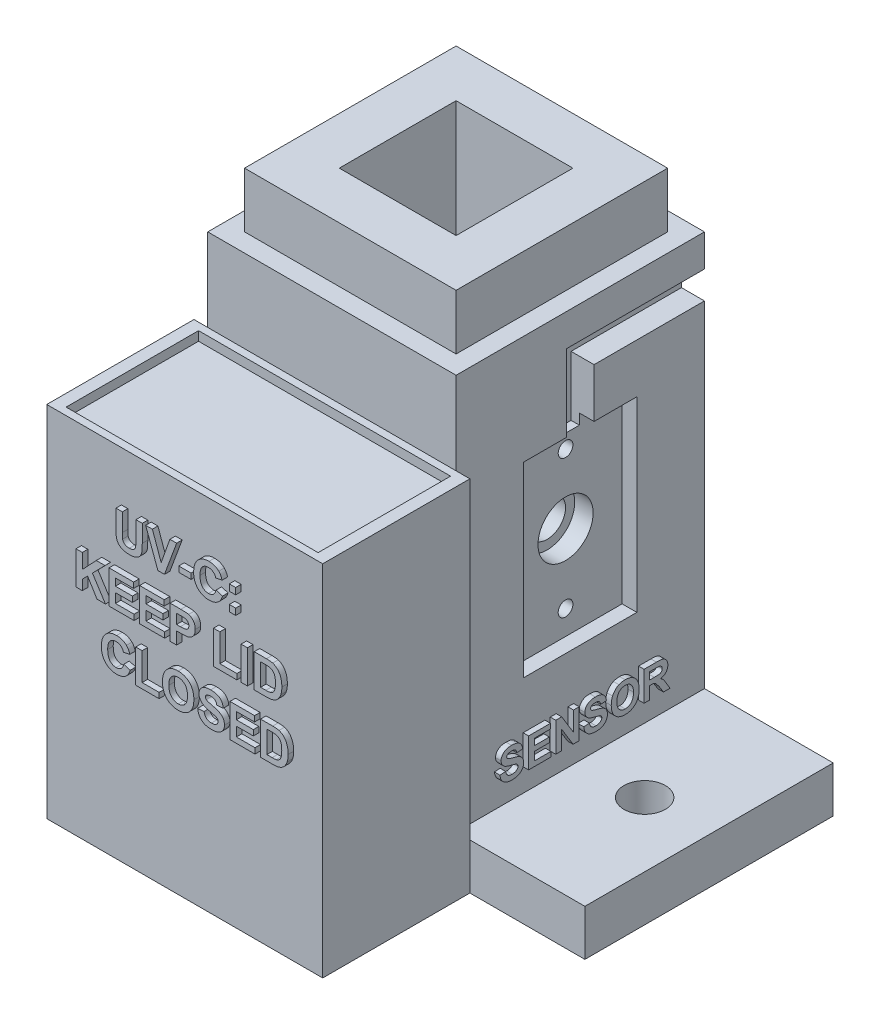
SolidWorks part; units mm, degrees
material "PETG"
ref_plane "Front Plane" through (0, 0, 0) normal (0, 0, 1) x (1, 0, 0)
ref_plane "Top Plane" through (0, 0, 0) normal (0, 1, 0) x (1, 0, 0)
ref_plane "Right Plane" through (0, 0, 0) normal (1, 0, 0) x (0, 0, -1)
other "Configuration Table"
sketch "Sketch1" plane through (0, 0, 0) normal (0, 1, 0) x (1, 0, 0)
  line L1 (-13.5, -13.5) -> (13.5, -13.5)
  line L2 (-13.5, -13.5) -> (-13.5, 13.5)
  line L3 (-13.5, 13.5) -> (13.5, 13.5)
  line L4 (13.5, -13.5) -> (13.5, 13.5)
  line L5 (-13.5, -13.5) -> (13.5, 13.5) construction
  line L6 (-13.5, 13.5) -> (13.5, -13.5) construction
  point P6 (0, 0)
  dimension "D1" = 27
  dimension "D2" = 27
extrude "Block" add sketch "Sketch1" along normal blind 54
sketch "Sketch2" plane through (0, 0, 0) normal (0, 1, 0) x (1, 0, 0)
  line L0 (-15, -29.5) -> (15, -29.5)
  line L1 (15, -29.5) -> (15, -13.5)
  line L2 (15, -13.5) -> (-15, -13.5)
  line L3 (-15, -13.5) -> (-15, -29.5)
extrude "Switch_Pillar" add sketch "Sketch2" along normal blind 39
sketch "Sketch3" plane through (0, 0, 0) normal (0, 1, 0) x (1, 0, 0)
  line L1 (-6.35, -6.35) -> (6.35, -6.35)
  line L2 (-6.35, -6.35) -> (-6.35, 6.35)
  line L3 (-6.35, 6.35) -> (6.35, 6.35)
  line L4 (6.35, -6.35) -> (6.35, 6.35)
  line L5 (-6.35, -6.35) -> (6.35, 6.35) construction
  line L6 (-6.35, 6.35) -> (6.35, -6.35) construction
  point P6 (0, 0)
  dimension "D1" = 12.7
  dimension "D2" = 12.7
extrude "Cuvette_Pocket" cut sketch "Sketch3" against normal blind 40 from offset 54
sketch "Sketch4" plane through (0, 0, 0) normal (0, 1, 0) x (1, 0, 0)
  line L0 (-18.5, -18.5) -> (18.5, -18.5)
  line L1 (18.5, -18.5) -> (18.5, 18.5)
  line L2 (18.5, 18.5) -> (-18.5, 18.5)
  line L3 (-18.5, 18.5) -> (-18.5, -18.5)
  line L4 (-11.5, -11.5) -> (11.5, -11.5)
  line L5 (11.5, -11.5) -> (11.5, 11.5)
  line L6 (11.5, 11.5) -> (-11.5, 11.5)
  line L7 (-11.5, 11.5) -> (-11.5, -11.5)
extrude "Lid_Step" cut sketch "Sketch4" against normal blind 6 from offset 54
sketch "Sketch5" plane through (0, 0, 0) normal (1, 0, 0) x (0, 0, -1)
  circle A0 centre (0, 26) radius 2
  dimension "D1" = 4
extrude "Optical_Apertures" cut sketch "Sketch5" along normal through all and the other way through all
sketch "Sketch6" plane through (0, 0, 0) normal (1, 0, 0) x (0, 0, -1)
  line L1 (-10.15, 15.85) -> (10.15, 15.85)
  line L2 (-10.15, 15.85) -> (-10.15, 36.15)
  line L3 (-10.15, 36.15) -> (10.15, 36.15)
  line L4 (10.15, 15.85) -> (10.15, 36.15)
  line L5 (-10.15, 15.85) -> (10.15, 36.15) construction
  line L6 (-10.15, 36.15) -> (10.15, 15.85) construction
  point P5 (0, 26)
  dimension "D1" = 20.3
  dimension "D2" = 20.3
extrude "LED_Recess" cut sketch "Sketch6" along normal blind 1.6 from offset 13.5
sketch "Sketch7" plane through (0, 0, 0) normal (1, 0, 0) x (0, 0, -1)
  line L1 (-6.15, 15.85) -> (6.15, 15.85)
  line L2 (-6.15, 15.85) -> (-6.15, 36.15)
  line L3 (-6.15, 36.15) -> (6.15, 36.15)
  line L4 (6.15, 15.85) -> (6.15, 36.15)
  line L5 (-6.15, 15.85) -> (6.15, 36.15) construction
  line L6 (-6.15, 36.15) -> (6.15, 15.85) construction
  point P5 (0, 26)
  dimension "D2" = 20.3
  dimension "D1" = 12.3
extrude "GUVA_Recess" cut sketch "Sketch7" against normal blind 1.6 from offset 13.5
sketch "Sketch8" plane through (0, 0, 0) normal (1, 0, 0) x (0, 0, -1)
  circle A0 centre (0, 26) radius 3
  dimension "D1" = 6
extrude "LED_Relief" cut sketch "Sketch8" along normal blind 2 from offset 11.9
sketch "Sketch9" plane through (0, 0, 0) normal (1, 0, 0) x (0, 0, -1)
  circle A0 centre (0, 26) radius 3
  dimension "D1" = 6
extrude "Sensor_Relief" cut sketch "Sketch9" against normal blind 2 from offset 11.9
sketch "Sketch10" plane through (0, 0, 0) normal (1, 0, 0) x (0, 0, -1)
  circle A0 centre (7, 19) radius 0.8
  circle A1 centre (-7, 33) radius 0.8
  dimension "D1" = 1.6
  dimension "D2" = 1.6
extrude "LED_Screw_Holes_M2" cut sketch "Sketch10" along normal blind 4 from offset 11.9
sketch "Sketch11" plane through (0, 0, 0) normal (1, 0, 0) x (0, 0, -1)
  circle A0 centre (0, 18.5) radius 0.8
  circle A1 centre (0, 33.5) radius 0.8
  dimension "D1" = 1.6
  dimension "D2" = 1.6
extrude "GUVA_Screw_Holes_M2" cut sketch "Sketch11" against normal blind 4 from offset 11.9
sketch "Sketch12" plane through (0, 0, 0) normal (1, 0, 0) x (0, 0, -1)
  line L0 (-1.5, 35) -> (-1.5, 44.5)
  line L1 (-1.5, 44.5) -> (14.5, 44.5)
  line L2 (14.5, 44.5) -> (14.5, 41.5)
  line L3 (14.5, 41.5) -> (1.5, 41.5)
  line L4 (1.5, 41.5) -> (1.5, 35)
  line L5 (1.5, 35) -> (-1.5, 35)
extrude "LED_Cable_Slot" cut sketch "Sketch12" along normal blind 2.5 from offset 13.5
sketch "Sketch13" plane through (0, 0, 0) normal (1, 0, 0) x (0, 0, -1)
  line L0 (-1.5, 35) -> (-1.5, 44.5)
  line L1 (-1.5, 44.5) -> (14.5, 44.5)
  line L2 (14.5, 44.5) -> (14.5, 41.5)
  line L3 (14.5, 41.5) -> (1.5, 41.5)
  line L4 (1.5, 41.5) -> (1.5, 35)
  line L5 (1.5, 35) -> (-1.5, 35)
extrude "GUVA_Cable_Slot" cut sketch "Sketch13" against normal blind 2.5 from offset 13.5
sketch "Sketch14" plane through (0, 0, 0) normal (0, 1, 0) x (1, 0, 0)
  line L1 (-13.7, -28.7) -> (13.7, -28.7)
  line L2 (-13.7, -28.7) -> (-13.7, -14.3)
  line L3 (-13.7, -14.3) -> (13.7, -14.3)
  line L4 (13.7, -28.7) -> (13.7, -14.3)
  line L5 (-13.7, -28.7) -> (13.7, -14.3) construction
  line L6 (-13.7, -14.3) -> (13.7, -28.7) construction
  point P5 (0, -21.5)
  dimension "D1" = 27.4
  dimension "D2" = 14.4
extrude "Reed_Switch_Seat" cut sketch "Sketch14" against normal blind 1 from offset 39
sketch "Sketch15" plane through (0, 0, 0) normal (0, 1, 0) x (1, 0, 0)
  line L0 (-27.5, -13.5) -> (-13.5, -13.5)
  line L1 (-13.5, -13.5) -> (-13.5, 13.5)
  line L2 (-13.5, 13.5) -> (-27.5, 13.5)
  line L3 (-27.5, 13.5) -> (-27.5, -13.5)
extrude "Foot_Left" add sketch "Sketch15" along normal blind 5
sketch "Sketch16" plane through (0, 0, 0) normal (0, 1, 0) x (1, 0, 0)
  line L0 (13.5, -13.5) -> (27.5, -13.5)
  line L1 (27.5, -13.5) -> (27.5, 13.5)
  line L2 (27.5, 13.5) -> (13.5, 13.5)
  line L3 (13.5, 13.5) -> (13.5, -13.5)
extrude "Foot_Right" add sketch "Sketch16" along normal blind 5
sketch "Sketch17" plane through (0, 0, 0) normal (0, 1, 0) x (1, 0, 0)
  circle A0 centre (-20.5, 0) radius 2.25
  circle A1 centre (20.5, 0) radius 2.25
  dimension "D1" = 4.5
  dimension "D2" = 4.5
extrude "Foot_Holes_M4" cut sketch "Sketch17" along normal blind 6 from offset 0.5
sketch "Sketch18" plane through (0, 0, 0) normal (1, 0, 0) x (0, 0, -1)
  text T0 "UV LED" font "Arial" height 3.2
extrude "Label_UV_LED" add sketch "Sketch18" against normal blind 0.6 from offset 13.5
sketch "Sketch19" plane through (0, 0, 0) normal (1, 0, 0) x (0, 0, -1)
  text T0 "SENSOR" font "Arial" height 3.2
extrude "Label_SENSOR" add sketch "Sketch19" along normal blind 0.6 from offset 13.5
sketch "Sketch20" plane through (0, 0, 0) normal (0, 0, 1) x (1, 0, 0)
  text T0 "UV-C:" font "Arial" height 3.6
extrude "Label_Warning_1" add sketch "Sketch20" along normal blind 0.6 from offset 29.5
sketch "Sketch21" plane through (0, 0, 0) normal (0, 0, 1) x (1, 0, 0)
  text T0 "KEEP LID" font "Arial" height 3.6
extrude "Label_Warning_2" add sketch "Sketch21" along normal blind 0.6 from offset 29.5
sketch "Sketch22" plane through (0, 0, 0) normal (0, 0, 1) x (1, 0, 0)
  text T0 "CLOSED" font "Arial" height 3.6
extrude "Label_Warning_3" add sketch "Sketch22" along normal blind 0.6 from offset 29.5
equation "\"Jar_OD\"= 90  'ASSUMED - Part G fallback - jar outer diameter"
equation "\"Jar_H\"= 120  'ASSUMED - Part G fallback - jar height"
equation "\"Pump_L\"= 45  'ASSUMED - Part G fallback"
equation "\"Pump_W\"= 24  'ASSUMED - Part G fallback"
equation "\"Pump_H\"= 33  'ASSUMED - Part G fallback"
equation "\"Pump_Outlet_OD\"= 7.5  'ASSUMED - Part G fallback"
equation "\"Tube_OD\"= 8  'ASSUMED - Part G fallback"
equation "\"Tube_ID\"= 6  'ASSUMED - Part G fallback"
equation "\"TDS_Body_Dia\"= 12  'ASSUMED - Part G fallback"
equation "\"TDS_Wet_Len\"= 45  'ASSUMED - Part G fallback - length in water"
equation "\"DS_Tube_Dia\"= 6  'ASSUMED - Part G fallback"
equation "\"DS_Tube_Len\"= 50  'ASSUMED - Part G fallback"
equation "\"ORP_Body_Dia\"= 12  'ASSUMED - Part G fallback"
equation "\"ORP_Body_Len\"= 150  'ASSUMED - Part G fallback"
equation "\"ORP_Cap_Dia\"= 16  'ASSUMED - Part G fallback"
equation "\"Turb_W\"= 33  'ASSUMED - Part G fallback - head width"
equation "\"Turb_D\"= 28  'ASSUMED - Part G fallback - head depth"
equation "\"Turb_H\"= 30  'ASSUMED - Part G fallback - head height"
equation "\"Turb_Slot_W\"= 10  'ASSUMED - Part G fallback - slot width"
equation "\"Flow_L\"= 62  'ASSUMED - Part G fallback YF-S201"
equation "\"Flow_W\"= 36  'ASSUMED - Part G fallback"
equation "\"Flow_H\"= 35  'ASSUMED - Part G fallback"
equation "\"Thread_G12_OD\"= 20.955  'ASSUMED - Part G fallback thread G1/2 (major diameter)"
equation "\"Valve_L\"= 75  'ASSUMED - Part G fallback"
equation "\"Valve_W\"= 45  'ASSUMED - Part G fallback"
equation "\"Valve_H\"= 60  'ASSUMED - Part G fallback"
equation "\"Tee_L\"= 40  'ASSUMED - Part G fallback - overall length"
equation "\"Tee_Branch_L\"= 25  'ASSUMED - Part G fallback"
equation "\"Tee_OD\"= 12  'ASSUMED - Part G fallback"
equation "\"Cuv_W\"= 12.5  'ASSUMED - old R3 cuvette (station suppressed in SS4)"
equation "\"Cuv_D\"= 12.5  'ASSUMED - old R3 cuvette (station suppressed in SS4)"
equation "\"Cuv_H\"= 45  'ASSUMED - old R3 cuvette (station suppressed in SS4)"
equation "\"LED_Board_L\"= 20  'ASSUMED - Part G fallback"
equation "\"LED_Board_W\"= 20  'ASSUMED - Part G fallback - LED at centre"
equation "\"GUVA_L\"= 20  'ASSUMED - Part G fallback"
equation "\"GUVA_W\"= 12  'ASSUMED - Part G fallback - sensor at centre"
equation "\"Reed_L\"= 27  'ASSUMED - Part G fallback MC-38 half"
equation "\"Reed_W\"= 14  'ASSUMED - Part G fallback"
equation "\"Reed_H\"= 8  'ASSUMED - Part G fallback"
equation "\"ESP_L\"= 51  'ASSUMED - Part G fallback"
equation "\"ESP_W\"= 28  'ASSUMED - Part G fallback"
equation "\"TFT_L\"= 58  'ASSUMED - Part G fallback - board"
equation "\"TFT_W\"= 35  'ASSUMED - Part G fallback - board"
equation "\"TFT_Win_L\"= 35  'ASSUMED - Part G fallback - visible window"
equation "\"TFT_Win_W\"= 28  'ASSUMED - Part G fallback - visible window"
equation "\"Relay_L\"= 50  'ASSUMED - Part G fallback"
equation "\"Relay_W\"= 26  'ASSUMED - Part G fallback"
equation "\"Relay_H\"= 19  'ASSUMED - Part G fallback"
equation "\"Mosfet_L\"= 34  'ASSUMED - Part G fallback"
equation "\"Mosfet_W\"= 17  'ASSUMED - Part G fallback"
equation "\"Mosfet_H\"= 12  'ASSUMED - Part G fallback"
equation "\"TDS_Board_L\"= 42  'ASSUMED - Part G fallback"
equation "\"TDS_Board_W\"= 32  'ASSUMED - Part G fallback"
equation "\"Turb_Board_L\"= 38  'ASSUMED - Part G fallback"
equation "\"Turb_Board_W\"= 28  'ASSUMED - Part G fallback"
equation "\"BNC_Thread_Dia\"= 9.5  'ASSUMED - Part G fallback"
equation "\"Plate_L\"= 420  'ASSUMED - Part G fallback"
equation "\"Plate_W\"= 297  'ASSUMED - Part G fallback"
equation "\"Plate_T\"= 6  'ASSUMED - Part G fallback"
equation "\"Probe_Clr\"= 0.3  'DESIGN VALUE - Part C rule 3 - printed probe hole = diameter + 0.3"
equation "\"Cuv_Clr\"= 0.2  'DESIGN VALUE - Part C rule 3 - cuvette pocket = size + 0.2"
equation "\"Label_H\"= 0.6  'DESIGN VALUE - Part D - raised label height"
equation "\"D1@Sketch1\" = 27.0"
equation "\"D2@Sketch1\" = 27.0"
equation "\"D1@Sketch3\" = \"Cuv_W\" + \"Cuv_Clr\""
equation "\"D2@Sketch3\" = \"Cuv_D\" + \"Cuv_Clr\""
equation "\"D1@Cuvette_Pocket\" = 40.0"
equation "\"D1@Sketch6\" = \"LED_Board_W\" + 0.3"
equation "\"D2@Sketch6\" = \"LED_Board_L\" + 0.3"
equation "\"D1@Sketch7\" = \"GUVA_W\" + 0.3"
equation "\"D2@Sketch7\" = \"GUVA_L\" + 0.3"
equation "\"D1@Sketch14\" = \"Reed_L\" + 0.4"
equation "\"D2@Sketch14\" = \"Reed_W\" + 0.4"
equation "\"D1@Label_UV_LED\" = \"Label_H\""
equation "\"D1@Label_SENSOR\" = \"Label_H\""
equation "\"D1@Label_Warning_1\" = \"Label_H\""
equation "\"D1@Label_Warning_2\" = \"Label_H\""
equation "\"D1@Label_Warning_3\" = \"Label_H\""
equation "\"Booster_L\"= 150  'ASSUMED - Part G fallback - booster pump"
equation "\"Booster_W\"= 95  'ASSUMED - Part G fallback"
equation "\"Booster_H\"= 100  'ASSUMED - Part G fallback"
equation "\"PTube_OD\"= 6.35  'ASSUMED - Part G fallback - product tube 1/4 inch"
equation "\"Qz_Out\"= 12  'ASSUMED - Part G fallback - quartz channel outside square"
equation "\"Qz_Path\"= 10  'ASSUMED - Part G fallback - quartz channel inside light path"
equation "\"Qz_L\"= 40  'ASSUMED - Part G fallback - quartz channel length"
equation "\"LED860_Dia\"= 5  'ASSUMED - Part G fallback - 860 nm LED"
equation "\"BPW_L\"= 5.4  'ASSUMED - Part G fallback - BPW34"
equation "\"BPW_W\"= 4.3  'ASSUMED - Part G fallback - BPW34"
equation "\"Cart_Dia\"= 50  'ASSUMED - Part G fallback - sediment and pre-carbon cartridges"
equation "\"Cart_L\"= 255  'ASSUMED - Part G fallback"
equation "\"UF_Dia\"= 50  'ASSUMED - Part G fallback - UF cartridge"
equation "\"UF_L\"= 260  'ASSUMED - Part G fallback"
equation "\"RO_Dia\"= 62  'ASSUMED - Part G fallback - RO membrane housing"
equation "\"RO_L\"= 300  'ASSUMED - Part G fallback"
equation "\"UVC_Dia\"= 40  'ASSUMED - Part G fallback - UV-C chamber"
equation "\"UVC_L\"= 300  'ASSUMED - Part G fallback"
equation "\"Tank_W\"= 260  'ASSUMED - Part G fallback - storage tank"
equation "\"Tank_D\"= 160  'ASSUMED - Part G fallback"
equation "\"Tank_H\"= 300  'ASSUMED - Part G fallback"
equation "\"Cab_W\"= 400  'ASSUMED - Part G fallback - purifier cabinet"
equation "\"Cab_D\"= 270  'ASSUMED - Part G fallback"
equation "\"Cab_H\"= 560  'ASSUMED - Part G fallback"
equation "\"ORP_Board_L\"= 40  'ASSUMED - Part G fallback - ORP buffer board"
equation "\"ORP_Board_W\"= 30  'ASSUMED - Part G fallback"
equation "\"Opt_Board_L\"= 50  'ASSUMED - Part G fallback - optical front-end board"
equation "\"Opt_Board_W\"= 40  'ASSUMED - Part G fallback"
equation "\"Buck_L\"= 43  'ASSUMED - Part G fallback - 12 V to 5 V buck module"
equation "\"Buck_W\"= 21  'ASSUMED - Part G fallback"
equation "\"Buck_H\"= 14  'ASSUMED - Part G fallback"
equation "\"BB_L\"= 165  'ASSUMED - Part G fallback - breadboard (As_Built_R3 only)"
equation "\"BB_W\"= 55  'ASSUMED - Part G fallback"
equation "\"BB_H\"= 10  'ASSUMED - Part G fallback"
